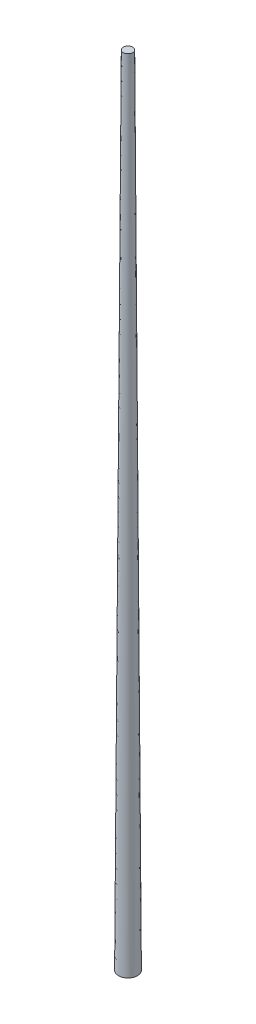
SolidWorks part; units mm, degrees
ref_plane "Plan de face" through (0, 0, 0) normal (0, 0, 1) x (1, 0, 0)
ref_plane "Plan de dessus" through (0, 0, 0) normal (0, 1, 0) x (1, 0, 0)
ref_plane "Plan de droite" through (0, 0, 0) normal (1, 0, 0) x (0, 0, -1)
sketch "Esquisse1" plane through (0, 0, 0) normal (0, 0, 1) x (1, 0, 0)
  line L0 (0, 0) -> (10, 0)
  line L1 (10, 0) -> (5, 840)
  line L2 (5, 840) -> (0, 840)
  line L3 (0, 840) -> (0, 0)
  dimension "D1" = 840
  dimension "D2" = 10
  dimension "D3" = 5
revolve "Révolution1" add sketch "Esquisse1" angle 360 about L3
